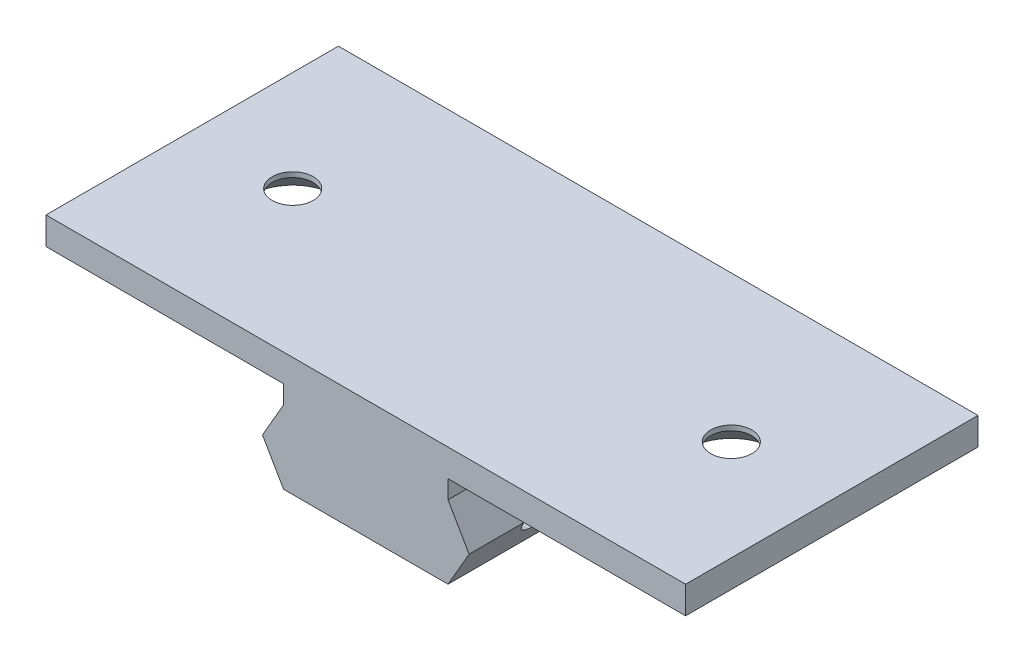
SolidWorks part; units mm, degrees
ref_plane "Front Plane" through (0, 0, 0) normal (0, 0, 1) x (1, 0, 0)
ref_plane "Top Plane" through (0, 0, 0) normal (0, 1, 0) x (1, 0, 0)
ref_plane "Right Plane" through (0, 0, 0) normal (1, 0, 0) x (0, 0, -1)
sketch "Sketch1" plane through (0, 0, 0) normal (0, 0, 1) x (1, 0, 0)
  line L0 (9, 0) -> (-9, 0)
  line L1 (-9, 0) -> (-11.3094, 4)
  line L2 (-11.3094, 4) -> (-9, 8)
  line L3 (-9, 8) -> (9, 8)
  line L4 (9, 8) -> (11.3094, 4)
  line L5 (11.3094, 4) -> (9, 0)
  dimension "D1" = 18
  dimension "D2" = 120
  dimension "D3" = 120
  dimension "D4" = 120
  dimension "D5" = 120
  dimension "D6" = 8
extrude "Boss-Extrude1" add sketch "Sketch1" along normal blind 32
sketch "Sketch2" plane through (0, 0, 0) normal (1, 0, 0) x (0, 0, -1)
  line L0 (-32, 4) -> (0, 4) construction
  line L1 (-32, 4) -> (-32, 8) construction
  circle A0 centre (-24, 4) radius 2
  dimension "D1" = 4
  dimension "D2" = 8
extrude "Cut-Extrude1" cut sketch "Sketch2" against normal through all both and the other way through all contours A0
pattern_linear "LPattern1" count 3 spacing 8 along (0, 0, -1) of "Cut-Extrude1"
sketch "Sketch3" plane through (0, 0, 0) normal (1, 0, 0) x (0, 0, -1)
  line L1 (-32, 8) -> (0, 8)
  line L2 (-32, 8) -> (-32, 10)
  line L3 (-32, 10) -> (0, 10)
  line L4 (0, 8) -> (0, 10)
  line L5 (-32, 8) -> (0, 10) construction
  line L6 (-32, 10) -> (0, 8) construction
  point P4 (-16, 9)
  dimension "D1" = 2
extrude "Boss-Extrude2" add sketch "Sketch3" along normal up to vertex (9 mm away) and the other way up to vertex (9 mm away) up to point (9, 8, 32) other way up to point (-9, 8, 32)
sketch "Sketch4" plane through (0, 0, 0) normal (1, 0, 0) x (0, 0, -1)
  line L1 (-32, 10) -> (0, 10)
  line L2 (-32, 10) -> (-32, 13)
  line L3 (-32, 13) -> (0, 13)
  line L4 (0, 10) -> (0, 13)
  line L5 (-32, 10) -> (0, 13) construction
  line L6 (-32, 13) -> (0, 10) construction
  point P4 (-16, 11.5)
  dimension "D1" = 3
extrude "Boss-Extrude3" add sketch "Sketch4" along normal blind 35 and the other way blind 35
sketch "Sketch5" plane through (0, 13, 0) normal (0, 1, 0) x (1, 0, 0)
  line L0 (0, -16) -> (24, -16) construction
  line L1 (-24, -16) -> (0, -16) construction
  line L3 (0, 0) -> (0, -32) construction
  line L6 (-35, -32) -> (35, -32) construction
  circle A0 centre (-24, -16) radius 2
  circle A1 centre (24, -16) radius 2
  dimension "D3" = 4
  dimension "D1" = 24
hole_wizard "CSK for M4 Countersunk Flat Head Screw1" positions "Skizze1" profile "Skizze3" countersink size "M4" standard "ISO" end condition through all
sketch "Skizze1" plane through (0, 10, 0) normal (0, -1, 0) x (-1, 0, 0)
  point P0 (-24, -16)
  point P3 (24, -16)
sketch "Skizze3" plane through (24, 10, 16) normal (1, 0, 0) x (0, 0, -1)
  line L0 (0, 0) -> (0, 3)
  line L1 (0, 3) -> (2.25, 3)
  line L2 (2.25, 3) -> (2.25, 2.45)
  line L3 (2.25, 2.45) -> (4.7, 0)
  line L5 (4.7, 0) -> (0, 0)
  line L6 (-2.25, 2.45) -> (-4.7, 0) construction
  line L11 (0, -6.35) -> (0, 107.95) construction
  dimension "Thru Hole Dia." = 4.5
  dimension "Thru Hole Depth" = 3
  dimension "Near C'Sink Dia." = 9.4
  dimension "Near C'Sink Angle" = 90
